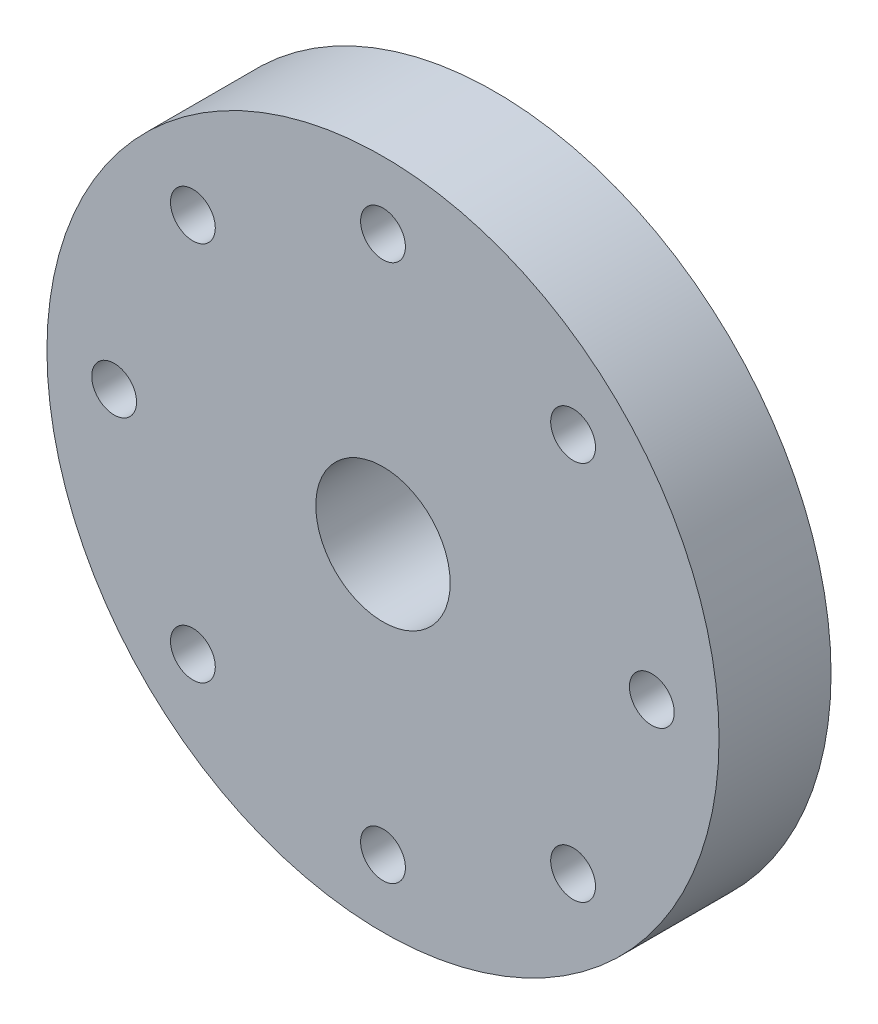
SolidWorks part; units mm, degrees
ref_plane "Front Plane" through (0, 0, 0) normal (0, 0, 1) x (1, 0, 0)
ref_plane "Top Plane" through (0, 0, 0) normal (0, 1, 0) x (1, 0, 0)
ref_plane "Right Plane" through (0, 0, 0) normal (1, 0, 0) x (0, 0, -1)
sketch "Sketch1" plane through (0, 0, 0) normal (0, 0, 1) x (1, 0, 0)
  circle A0 centre (-0.0415, -0.1086) radius 15
  circle A1 centre (-0.0415, 11.8914) radius 1
  circle A2 centre (8.4438, 8.3767) radius 1
  circle A3 centre (11.9585, -0.1086) radius 1
  circle A4 centre (-0.0415, -12.1086) radius 1
  circle A5 centre (8.4438, -8.5939) radius 1
  circle A6 centre (-8.5268, -8.5939) radius 1
  circle A7 centre (-12.0415, -0.1086) radius 1
  circle A8 centre (-8.5268, 8.3767) radius 1
  circle A9 centre (-0.0415, -0.1086) radius 3
  point P19 (0, 0)
extrude "Boss-Extrude1" add sketch "Sketch1" along normal blind 5
